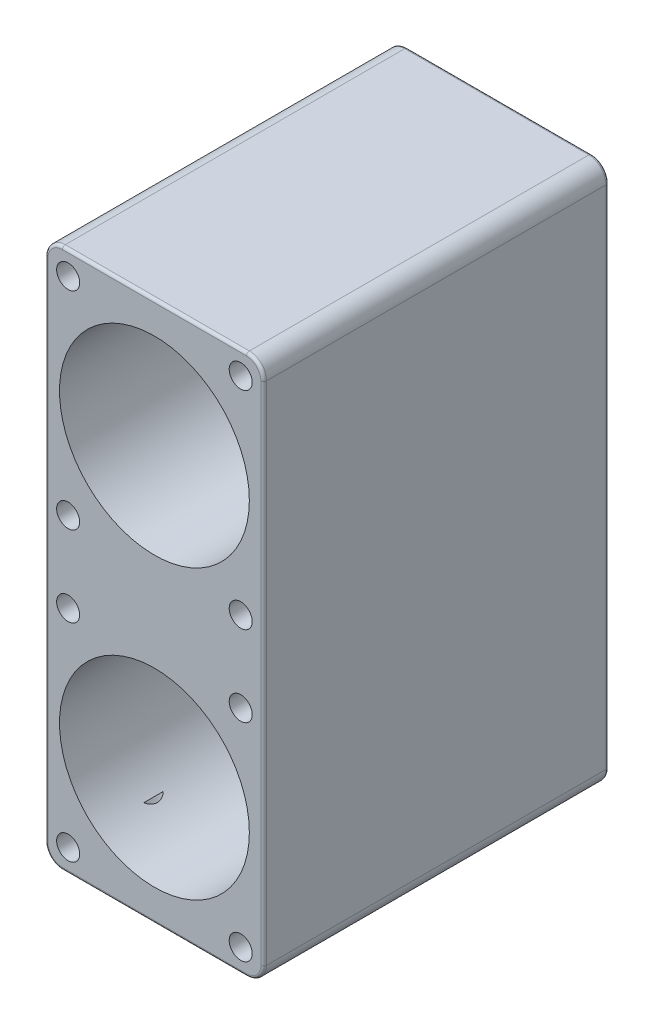
SolidWorks part; units mm, degrees
ref_plane "Front Plane" through (0, 0, 0) normal (0, 0, 1) x (1, 0, 0)
ref_plane "Top Plane" through (0, 0, 0) normal (0, 1, 0) x (1, 0, 0)
ref_plane "Right Plane" through (0, 0, 0) normal (1, 0, 0) x (0, 0, -1)
sketch "Sketch1" plane through (0, 0, 0) normal (0, 0, 1) x (1, 0, 0)
  line L0 (-344.3341, 0) -> (344.3341, 0) construction
  line L1 (-406.4, 1193.8) -> (406.4, 1193.8)
  line L2 (-482.6, 1117.6) -> (-482.6, -1117.6)
  line L3 (-406.4, -1193.8) -> (406.4, -1193.8)
  line L4 (482.6, 1117.6) -> (482.6, -1117.6)
  line L5 (-482.6, 1193.8) -> (482.6, -1193.8) construction
  line L6 (-482.6, -1193.8) -> (482.6, 1193.8) construction
  line L7 (-344.3341, 152.4) -> (344.3341, 152.4) construction
  arc A0 (406.4, -1193.8) -> (482.6, -1117.6) centre (406.4, -1117.6) ccw
  arc A1 (-482.6, -1117.6) -> (-406.4, -1193.8) centre (-406.4, -1117.6) ccw
  arc A2 (406.4, 1193.8) -> (482.6, 1117.6) centre (406.4, 1117.6) cw
  arc A3 (-406.4, 1193.8) -> (-482.6, 1117.6) centre (-406.4, 1117.6) ccw
  circle A4 centre (0, 635) radius 419.1
  circle A5 centre (0, -635) radius 419.1
  point P0 (0, 0)
  point P25 (0, 0)
  dimension "D3" = 76.2
  dimension "D4" = 838.2
  dimension "D5" = 838.2
  dimension "D1" = 2387.6
  dimension "D2" = 965.2
  dimension "D6" = 635
  dimension "D7" = 635
  dimension "D8" = 152.4
extrude "Boss-Extrude1" add sketch "Sketch1" along normal mid plane 1524
sketch "Sketch2" plane through (0, 0, 762) normal (0, 0, 1) x (1, 0, 0)
  line L0 (-482.6, 0) -> (482.6, 0) construction
  line L1 (482.6, -1117.6) -> (482.6, 1117.6) construction
  circle A0 centre (-381, 177.8) radius 50.8
  circle A1 centre (-381, -177.8) radius 50.8
  circle A2 centre (381, 177.8) radius 50.8
  circle A3 centre (381, -177.8) radius 50.8
  point P6 (0, 0)
  dimension "D1" = 101.6
  dimension "D2" = 177.8
  dimension "D3" = 177.8
  dimension "D4" = 381
  dimension "D5" = 381
extrude "Cut-Extrude1" cut sketch "Sketch2" against normal blind 254
sketch "Sketch3" plane through (0, 0, 762) normal (0, 0, 1) x (1, 0, 0)
  line L0 (0, -635) -> (0, -1193.8) construction
  line L1 (-406.4, -1193.8) -> (406.4, -1193.8) construction
  circle A0 centre (-381, -1092.2) radius 50.8
  circle A1 centre (381, -1092.2) radius 50.8
  point P0 (0, -635)
  dimension "D2" = 101.6
  dimension "D1" = 457.2
  dimension "D3" = 381
  dimension "D4" = 381
  dimension "D5" = 457.2
extrude "Cut-Extrude2" cut sketch "Sketch3" against normal blind 177.8
sketch "Sketch4" plane through (0, 0, 762) normal (0, 0, 1) x (1, 0, 0)
  line L0 (0, 635) -> (0, 1193.8) construction
  line L1 (406.4, 1193.8) -> (-406.4, 1193.8) construction
  line L2 (0, 635) -> (-482.6, 635) construction
  line L3 (-482.6, 1117.6) -> (-482.6, -1117.6) construction
  circle A0 centre (-381, 1092.2) radius 50.8
  circle A1 centre (381, 1092.2) radius 50.8
  point P0 (0, 635)
  dimension "D1" = 101.6
  dimension "D2" = 457.2
  dimension "D3" = 457.2
  dimension "D4" = 381
  dimension "D5" = 381
extrude "Cut-Extrude3" cut sketch "Sketch4" against normal through all
fillet "Fillet1" radius 12.7 16 edges at (460.2815, -1171.4815, -762) (0, -1193.8, -762) (-460.2815, -1171.4815, -762) (-482.6, 0, -762) (-460.2815, 1171.4815, -762) (0, 1193.8, -762) (460.2815, 1171.4815, -762) (460.2815, -1171.4815, 762) (0, -1193.8, 762) (-460.2815, -1171.4815, 762) (-482.6, 0, 762) (-460.2815, 1171.4815, 762) (0, 1193.8, 762) (460.2815, 1171.4815, 762) (482.6, 0, -762) (482.6, 0, 762)
sketch "Sketch5" plane through (0, -1193.8, 0) normal (0, -1, 0) x (1, 0, 0)
  line L1 (0, 875.7107) -> (0, -875.7107) construction
  line L3 (-406.4, 762) -> (406.4, 762) construction
  circle A0 centre (-304.8, 508) radius 63.5
  circle A1 centre (304.8, 508) radius 63.5
  circle A2 centre (-304.8, -508) radius 63.5
  circle A3 centre (304.8, -508) radius 63.5
  point P11 (0, 0)
  point P15 (0, -12.6351)
  dimension "D1" = 127
  dimension "D2" = 304.8
  dimension "D3" = 304.8
  dimension "D4" = 1016
  dimension "D5" = 254
extrude "Cut-Extrude4" cut sketch "Sketch5" against normal blind 228.6
sketch "Sketch7" plane through (0, 0, -762) normal (0, 0, -1) x (-1, 0, 0)
  line L0 (-386.7641, 0) -> (386.7641, 0) construction
  line L2 (-482.6, -1117.6) -> (-482.6, 1117.6) construction
  line L3 (482.6, 1117.6) -> (482.6, -1117.6) construction
  circle A0 centre (-355.6, 152.4) radius 50.8
  circle A1 centre (-355.6, -152.4) radius 50.8
  circle A2 centre (355.6, 152.4) radius 50.8
  circle A3 centre (355.6, -152.4) radius 50.8
  point P4 (0, 0)
  dimension "D5" = 101.6
  dimension "D1" = 152.4
  dimension "D2" = 152.4
  dimension "D3" = 152.4
  dimension "D4" = 127
  dimension "D6" = 127
extrude "Cut-Extrude5" cut sketch "Sketch7" against normal blind 254
